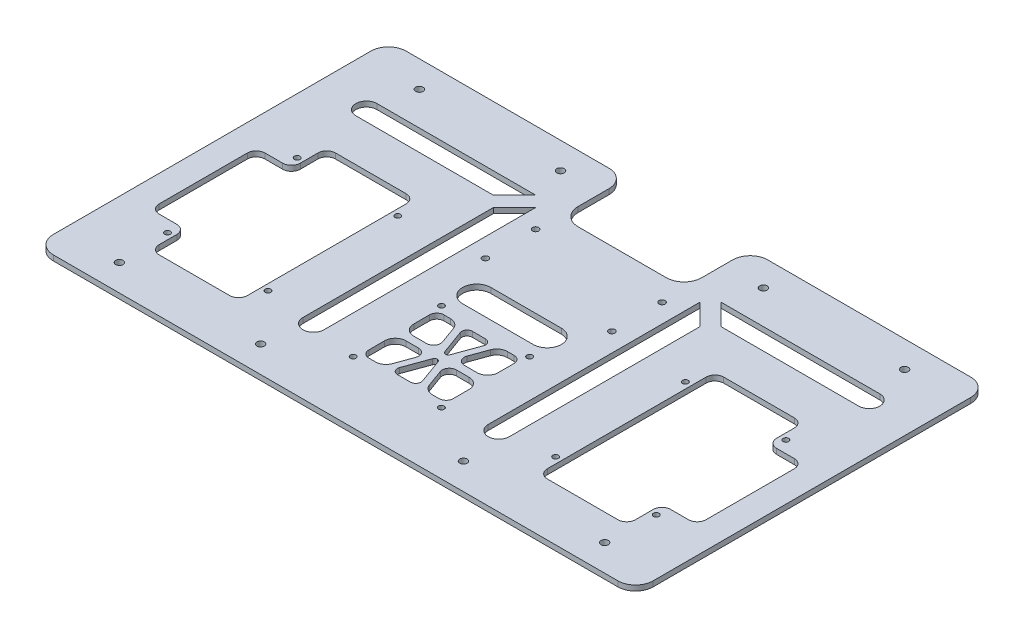
SolidWorks part; units mm, degrees
material "1023 碳钢板 (SS)"
ref_plane "前视基准面" through (0, 0, 0) normal (0, 0, 1) x (1, 0, 0)
ref_plane "上视基准面" through (0, 0, 0) normal (0, 1, 0) x (1, 0, 0)
ref_plane "右视基准面" through (0, 0, 0) normal (1, 0, 0) x (0, 0, -1)
sketch "草图1" plane through (0, 0, 0) normal (0, 1, 0) x (1, 0, 0)
  line L1 (-217.5, 100) -> (217.5, 100)
  line L2 (-217.5, 100) -> (-217.5, -100)
  line L3 (-217.5, -100) -> (217.5, -100)
  line L4 (217.5, 100) -> (217.5, -100)
  line L5 (-217.5, 100) -> (217.5, -100) construction
  line L6 (-217.5, -100) -> (217.5, 100) construction
  point P0 (0, 0)
  dimension "D1" = 200
  dimension "D2" = 435
extrude "凸台-拉伸1" add sketch "草图1" along normal blind 3
sketch "草图2" plane through (0, 3, 0) normal (0, 1, 0) x (1, 0, 0)
  line L0 (0, -1000) -> (0, 49000) construction
  line L1 (217.5, 100) -> (-217.5, 100) construction
  line L2 (81.5, 16.75) -> (138.5, 16.75) construction
  line L3 (81.5, 16.75) -> (81.5, -56.75) construction
  line L4 (81.5, -56.75) -> (138.5, -56.75) construction
  line L5 (138.5, 16.75) -> (138.5, -56.75) construction
  line L6 (81.5, 16.75) -> (138.5, -56.75) construction
  line L7 (81.5, -56.75) -> (138.5, 16.75) construction
  line L8 (-81.5, -56.75) -> (-138.5, 16.75) construction
  line L9 (-81.5, 16.75) -> (-138.5, -56.75) construction
  line L10 (-138.5, 16.75) -> (-138.5, -56.75) construction
  line L11 (-81.5, -56.75) -> (-138.5, -56.75) construction
  line L12 (-81.5, 16.75) -> (-81.5, -56.75) construction
  line L13 (-81.5, 16.75) -> (-138.5, 16.75) construction
  circle A0 centre (138.5, 16.75) radius 1.6
  circle A1 centre (138.5, -56.75) radius 1.6
  circle A2 centre (81.5, -56.75) radius 1.6
  circle A3 centre (81.5, 16.75) radius 1.6
  circle A4 centre (-81.5, 16.75) radius 1.6
  circle A5 centre (-81.5, -56.75) radius 1.6
  circle A6 centre (-138.5, -56.75) radius 1.6
  circle A7 centre (-138.5, 16.75) radius 1.6
  point P1 (110, -20)
  point P22 (-110, -20)
  dimension "D5" = 3.2
  dimension "D6" = 3.2
  dimension "D7" = 3.2
  dimension "D8" = 3.2
  dimension "D1" = 120
  dimension "D2" = 110
  dimension "D3" = 57
  dimension "D4" = 73.5
extrude "切除-拉伸1" cut sketch "草图2" against normal blind 157
sketch "草图3" plane through (0, 3, 0) normal (0, 1, 0) x (1, 0, 0)
  line L0 (-138.5, 16.75) -> (-81.5, 16.75) construction
  line L1 (-110, -923.25) -> (-110, 49076.75) construction
  line L2 (-138.5, 16.75) -> (-81.5, -56.75) construction
  line L3 (0, -1000) -> (0, 49000) construction
  line L4 (-135, 30) -> (-85, 30)
  line L5 (-135, 30) -> (-135, -70)
  line L6 (-135, -70) -> (-85, -70)
  line L7 (-85, 30) -> (-85, -70)
  line L8 (-135, 30) -> (-85, -70) construction
  line L9 (-135, -70) -> (-85, 30) construction
  line L10 (135, -70) -> (85, 30) construction
  line L11 (135, 30) -> (85, -70) construction
  line L12 (138.5, 16.75) -> (81.5, -56.75) construction
  line L13 (138.5, 16.75) -> (81.5, 16.75) construction
  line L14 (85, 30) -> (85, -70)
  line L15 (135, -70) -> (85, -70)
  line L16 (135, 30) -> (135, -70)
  line L17 (135, 30) -> (85, 30)
  point P3 (-110, -20)
  point P5 (-110, 16.75)
  point P24 (110, -20)
  dimension "D1" = 100
  dimension "D2" = 50
extrude "切除-拉伸2" cut sketch "草图3" against normal blind 157
sketch "草图5" plane through (0, 3, 0) normal (0, 1, 0) x (1, 0, 0)
  line L0 (-1060, -20) -> (48940, -20) construction
  line L1 (-135, 30) -> (-135, -70) construction
  line L2 (0, -1000) -> (0, 49000) construction
  line L3 (-155, 10) -> (-135, 10)
  line L4 (-155, 10) -> (-155, -50)
  line L5 (-155, -50) -> (-135, -50)
  line L6 (-135, 10) -> (-135, -50)
  line L7 (-155, 10) -> (-135, -50) construction
  line L8 (-155, -50) -> (-135, 10) construction
  line L9 (155, -50) -> (135, 10) construction
  line L10 (155, 10) -> (135, -50) construction
  line L11 (135, 10) -> (135, -50)
  line L12 (155, -50) -> (135, -50)
  line L13 (155, 10) -> (155, -50)
  line L14 (155, 10) -> (135, 10)
  point P1 (-145, -20)
  point P5 (-135, -20)
  point P17 (145, -20)
  dimension "D1" = 60
  dimension "D2" = 10
extrude "切除-拉伸3" cut sketch "草图5" against normal blind 157
fillet "圆角1" radius 5 16 edges at (155, 1.5, 50) (135, 1.5, 70) (85, 1.5, -30) (85, 1.5, 70) (135, 1.5, 50) (135, 1.5, -10) (135, 1.5, -30) (155, 1.5, -10) (-85, 1.5, 70) (-135, 1.5, 70) (-135, 1.5, 50) (-155, 1.5, 50) (-155, 1.5, -10) (-85, 1.5, -30) (-135, 1.5, -30) (-135, 1.5, -10)
sketch "草图6" plane through (0, 3, 0) normal (0, 1, 0) x (1, 0, 0)
  line L0 (0, -1000) -> (0, 49000) construction
  line L1 (-40, -85) -> (40, -85)
  line L2 (-31.4905, -2.5) -> (31.4905, -2.5)
  line L3 (40, -12.5) -> (40, -85)
  line L4 (31.4905, -2.5) -> (40, -12.5)
  line L5 (-31.4905, -2.5) -> (-40, -12.5)
  line L6 (-40, -12.5) -> (-40, -85)
  line L7 (-217.5, -100) -> (217.5, -100) construction
  point P6 (0, -85)
  point P7 (0, -85)
  point P12 (0, -2.5)
  dimension "D1" = 40
  dimension "D2" = 72.5
  dimension "D3" = 10
  dimension "D4" = 15
extrude "切除-拉伸4" [suppressed] cut sketch "草图6" against normal blind 157
sketch "草图7" plane through (0, 3, 0) normal (0, 1, 0) x (1, 0, 0)
  line L0 (-1068.651, -70) -> (48931.349, -70) construction
  line L1 (-217.5, -100) -> (217.5, -100) construction
  circle A0 centre (55, -70) radius 1.6
  circle A1 centre (-55, -70) radius 1.6
  circle A2 centre (55, -20) radius 1.6
  circle A3 centre (-55, -20) radius 1.6
  dimension "D2" = 3.2
  dimension "D4" = 3.2
  dimension "D7" = 3.2
  dimension "D8" = 3.2
  dimension "D1" = 30
  dimension "D3" = 55
  dimension "D5" = 110
  dimension "D6" = 50
  dimension "D9" = 50
  dimension "D10" = 110
extrude "切除-拉伸5" [suppressed] cut sketch "草图7" against normal blind 157
sketch "草图8" plane through (0, 3, 0) normal (0, 1, 0) x (1, 0, 0)
  line L1 (217.5, -100) -> (217.5, 100) construction
  line L2 (217.5, 100) -> (-217.5, 100) construction
  line L3 (-35.85, 49.25) -> (35.85, 49.25) construction
  line L4 (-35.85, 49.25) -> (-35.85, 20.75) construction
  line L5 (-35.85, 20.75) -> (35.85, 20.75) construction
  line L6 (35.85, 49.25) -> (35.85, 20.75) construction
  line L7 (-35.85, 49.25) -> (35.85, 20.75) construction
  line L8 (-35.85, 20.75) -> (35.85, 49.25) construction
  circle A0 centre (-35.85, 49.25) radius 1.75
  circle A1 centre (35.85, 49.25) radius 1.75
  circle A2 centre (-35.85, 20.75) radius 1.75
  circle A3 centre (35.85, 20.75) radius 1.75
  point P0 (0, 35)
  dimension "D4" = 3.5
  dimension "D5" = 3.5
  dimension "D6" = 3.5
  dimension "D7" = 3.5
  dimension "D1" = 217.5
  dimension "D2" = 71.7
  dimension "D3" = 28.5
  dimension "D8" = 65
sketch "草图9" plane through (0, 3, 0) normal (0, 1, 0) x (1, 0, 0)
  line L0 (-1217.5, -85) -> (48782.5, -85) construction
  line L2 (-217.5, -100) -> (217.5, -100) construction
  line L3 (0, -1000) -> (0, 49000) construction
  line L4 (-1000, 0) -> (49000, 0) construction
  line L5 (-217.5, 100) -> (-217.5, -100) construction
  circle A0 centre (-137.5, -85) radius 2.1
  circle A2 centre (-57.5, -85) radius 2.1
  circle A3 centre (57.5, -85) radius 2.1
  circle A5 centre (137.5, -85) radius 2.1
  circle A6 centre (137.5, 85) radius 2.1
  circle A8 centre (57.5, 85) radius 2.1
  circle A9 centre (-57.5, 85) radius 2.1
  circle A11 centre (-137.5, 85) radius 2.1
  dimension "D2" = 4.2
  dimension "D3" = 80
  dimension "D7" = 4.2
  dimension "D1" = 15
  dimension "D4" = 80
extrude "切除-拉伸6" cut sketch "草图9" against normal blind 10
sketch "草图10" plane through (0, 3, 0) normal (0, 1, 0) x (1, 0, 0)
  line L0 (0, -1000) -> (0, 49000) construction
  line L1 (-217.5, -100) -> (217.5, -100) construction
  line L2 (-25, -15) -> (25, -15) construction
  line L3 (-25, -15) -> (-25, -65) construction
  line L4 (-25, -65) -> (25, -65) construction
  line L5 (25, -15) -> (25, -65) construction
  line L6 (-25, -15) -> (25, -65) construction
  line L7 (-25, -65) -> (25, -15) construction
  circle A0 centre (-25, -15) radius 1.6
  circle A1 centre (25, -15) radius 1.6
  circle A2 centre (25, -65) radius 1.6
  circle A3 centre (-25, -65) radius 1.6
  point P1 (0, -40)
  dimension "D4" = 3.2
  dimension "D5" = 3.2
  dimension "D6" = 3.2
  dimension "D7" = 3.2
  dimension "D1" = 50
  dimension "D2" = 50
  dimension "D3" = 60
extrude "切除-拉伸7" cut sketch "草图10" against normal blind 10
fillet "圆角2" [suppressed] radius 10
extrude "切除-拉伸8" cut sketch "草图8" against normal blind 10
sketch "草图12" plane through (0, 3, 0) normal (0, 1, 0) x (1, 0, 0)
  line L1 (-251.9202, 129.8695) -> (-3.3421, 129.8695)
  line L2 (-251.9202, 129.8695) -> (-251.9202, -149.5666)
  line L3 (-251.9202, -149.5666) -> (-3.3421, -149.5666)
  line L4 (-3.3421, 129.8695) -> (-3.3421, -149.5666)
  line L5 (-3.3421, -53.564) -> (257.665, -53.564)
  line L6 (-3.3421, -53.564) -> (-3.3421, -149.5666)
  line L7 (-3.3421, -149.5666) -> (257.665, -149.5666)
  line L8 (257.665, -53.564) -> (257.665, -149.5666)
  line L9 (-3.3421, 129.8695) -> (241.8074, 129.8695)
  line L10 (-3.3421, 129.8695) -> (-3.3421, 96.8686)
  line L11 (-3.3421, 96.8686) -> (241.8074, 96.8686)
  line L12 (241.8074, 129.8695) -> (241.8074, 96.8686)
extrude "切除-拉伸10" [suppressed] cut sketch "草图12" against normal blind 10 contours L4 L1 L2 L3 | L12 L9 L4 L11 | L8 L5 L4 L7
sketch "草图13" plane through (0, 3, 0) normal (0, 1, 0) x (1, 0, 0)
  line L0 (-1000, 0) -> (49000, 0) construction
  line L1 (-52.5007, 60) -> (-142.5007, 60) construction
  line L2 (-52.5007, 54) -> (-142.5007, 54)
  line L3 (-52.5007, 66) -> (-142.5007, 66)
  line L5 (0, -1000) -> (0, 49000) construction
  line L6 (52.5007, 60) -> (142.5007, 60) construction
  line L7 (52.5007, 54) -> (142.5007, 54)
  line L8 (52.5007, 66) -> (142.5007, 66)
  line L9 (-155, 5) -> (-155, -45) construction
  line L10 (-52.5007, 60) -> (52.5007, 60) construction
  line L11 (-52.5007, 60) -> (-52.5007, -60) construction
  line L12 (-52.5007, -60) -> (52.5007, -60) construction
  line L13 (52.5007, 60) -> (52.5007, -60) construction
  line L14 (-52.5007, 60) -> (52.5007, -60) construction
  line L15 (-52.5007, -60) -> (52.5007, 60) construction
  line L16 (-52.5007, 60) -> (-52.5007, -60) construction
  line L17 (-46.5007, 60) -> (-46.5007, -60)
  line L18 (-58.5007, 60) -> (-58.5007, -60)
  line L19 (52.5007, 60) -> (52.5007, -60) construction
  line L20 (52.5007, 60) -> (52.5007, -60) construction
  line L21 (46.5007, 60) -> (46.5007, -60)
  line L22 (58.5007, 60) -> (58.5007, -60)
  line L23 (-20, 0) -> (20, 0) construction
  line L24 (-20, 8) -> (20, 8)
  line L25 (-20, -8) -> (20, -8)
  line L51 (-223.1142, 125.8648) -> (-170, 125.8648)
  line L52 (-223.1142, 125.8648) -> (-223.1142, -114.639)
  line L53 (-223.1142, -114.639) -> (-170, -114.639)
  line L54 (-170, 125.8648) -> (-170, -114.639)
  line L55 (170, 125.8648) -> (170, -114.639)
  line L56 (223.1142, -114.639) -> (170, -114.639)
  line L57 (223.1142, 125.8648) -> (223.1142, -114.639)
  line L58 (223.1142, 125.8648) -> (170, 125.8648)
  arc A0 (-52.5007, 54) -> (-52.5007, 66) centre (-52.5007, 60) ccw
  arc A1 (-142.5007, 66) -> (-142.5007, 54) centre (-142.5007, 60) ccw
  arc A2 (52.5007, 54) -> (52.5007, 66) centre (52.5007, 60) cw
  arc A3 (142.5007, 66) -> (142.5007, 54) centre (142.5007, 60) cw
  arc A4 (-46.5007, 60) -> (-58.5007, 60) centre (-52.5007, 60) ccw
  arc A5 (-58.5007, -60) -> (-46.5007, -60) centre (-52.5007, -60) ccw
  arc A6 (46.5007, 60) -> (58.5007, 60) centre (52.5007, 60) cw
  arc A7 (58.5007, -60) -> (46.5007, -60) centre (52.5007, -60) cw
  arc A8 (-20, 8) -> (-20, -8) centre (-20, 0) ccw
  arc A9 (20, -8) -> (20, 8) centre (20, 0) ccw
  point P4 (-97.5007, 60)
  point P11 (97.5007, 60)
  point P29 (-52.5007, 0)
  point P34 (52.5007, 0)
  point P41 (0, 0)
  dimension "D2" = 90
  dimension "D7" = 6
  dimension "D10" = 8
  dimension "D3" = 6
  dimension "D4" = 15
  dimension "D5" = 120
  dimension "D6" = 0
  dimension "D9" = 0
extrude "切除-拉伸11" cut sketch "草图13" against normal blind 10
sketch "草图14" plane through (0, 3, 0) normal (0, 1, 0) x (1, 0, 0)
  line L0 (0, -1000) -> (0, 49000) construction
  line L2 (170, 100) -> (-170, 100) construction
  line L3 (-35, 137.5) -> (35, 137.5)
  line L4 (-35, 137.5) -> (-35, 62.5)
  line L5 (-35, 62.5) -> (35, 62.5)
  line L6 (35, 137.5) -> (35, 62.5)
  line L7 (-35, 137.5) -> (35, 62.5) construction
  line L8 (-35, 62.5) -> (35, 137.5) construction
  point P1 (0, 100)
  dimension "D1" = 75
  dimension "D2" = 70
extrude "切除-拉伸12" cut sketch "草图14" against normal blind 64.5 contours L6 L3 L4 L5
fillet "圆角4" radius 10 8 edges at (-35, 1.5, -62.5) (35, 1.5, -62.5) (-35, 1.5, -100) (35, 1.5, -100) (170, 1.5, 100) (-170, 1.5, 100) (170, 1.5, -100) (-170, 1.5, -100)
sketch "草图15" plane through (0, 3, 0) normal (0, 1, 0) x (1, 0, 0)
  line L3 (6.5346, -57.2239) -> (1.5635, -43.566)
  line L4 (-23.9154, -22.75) -> (-23.9154, -31.75)
  line L5 (-17.9154, -37.75) -> (-10.7126, -37.75)
  line L6 (-6.9538, -32.3819) -> (-10.4785, -22.6979)
  line L7 (-16.1167, -18.75) -> (-19.9154, -18.75)
  line L8 (-23.9154, -22.75) -> (-23.9154, -31.75)
  line L9 (-17.9154, -37.75) -> (-10.7126, -37.75)
  line L10 (-6.9538, -32.3819) -> (-10.4785, -22.6979)
  line L11 (-16.1167, -18.75) -> (-19.9154, -18.75)
  line L12 (-10.4785, -57.3021) -> (-6.9538, -47.6181)
  line L13 (-19.9154, -61.25) -> (-16.1167, -61.25)
  line L14 (-23.9154, -48.25) -> (-23.9154, -57.25)
  line L15 (-10.7126, -42.25) -> (-17.9154, -42.25)
  line L16 (-10.4785, -57.3021) -> (-6.9538, -47.6181)
  line L17 (-19.9154, -61.25) -> (-16.1167, -61.25)
  line L18 (-23.9154, -48.25) -> (-23.9154, -57.25)
  line L19 (-10.7126, -42.25) -> (-17.9154, -42.25)
  line L20 (-1.5635, -43.566) -> (-6.5346, -57.2239)
  line L21 (-3.7156, -61.25) -> (3.7156, -61.25)
  line L22 (6.5346, -57.2239) -> (1.5635, -43.566)
  line L23 (-1.5635, -43.566) -> (-6.5346, -57.2239)
  line L24 (-3.7156, -61.25) -> (3.7156, -61.25)
  line L25 (1.5635, -36.434) -> (6.5346, -22.7761)
  line L26 (23.9154, -31.75) -> (23.9154, -22.75)
  line L27 (10.7126, -37.75) -> (17.9154, -37.75)
  line L28 (10.4785, -22.6979) -> (6.9538, -32.3819)
  line L29 (19.9154, -18.75) -> (16.1167, -18.75)
  line L30 (23.9154, -31.75) -> (23.9154, -22.75)
  line L31 (10.7126, -37.75) -> (17.9154, -37.75)
  line L32 (10.4785, -22.6979) -> (6.9538, -32.3819)
  line L33 (19.9154, -18.75) -> (16.1167, -18.75)
  line L34 (-6.5346, -22.7761) -> (-1.5635, -36.434)
  line L35 (3.7156, -18.75) -> (-3.7156, -18.75)
  line L36 (1.5635, -36.434) -> (6.5346, -22.7761)
  line L37 (-6.5346, -22.7761) -> (-1.5635, -36.434)
  line L38 (3.7156, -18.75) -> (-3.7156, -18.75)
  line L40 (23.9154, -57.25) -> (23.9154, -48.25)
  line L41 (17.9154, -42.25) -> (10.7126, -42.25)
  line L42 (6.9538, -47.6181) -> (10.4785, -57.3021)
  line L43 (16.1167, -61.25) -> (19.9154, -61.25)
  line L44 (23.9154, -57.25) -> (23.9154, -48.25)
  line L45 (17.9154, -42.25) -> (10.7126, -42.25)
  line L46 (6.9538, -47.6181) -> (10.4785, -57.3021)
  line L47 (16.1167, -61.25) -> (19.9154, -61.25)
  arc A0 (-23.9154, -31.75) -> (-17.9154, -37.75) centre (-17.9154, -31.75) ccw construction
  arc A1 (-23.9154, -31.75) -> (-17.9154, -37.75) centre (-17.9154, -31.75) ccw
  arc A6 (-19.9154, -18.75) -> (-23.9154, -22.75) centre (-19.9154, -22.75) ccw
  arc A7 (-23.9154, -31.75) -> (-17.9154, -37.75) centre (-17.9154, -31.75) ccw
  arc A8 (-10.7126, -37.75) -> (-6.9538, -32.3819) centre (-10.7126, -33.75) ccw
  arc A9 (-10.4785, -22.6979) -> (-16.1167, -18.75) centre (-16.1167, -24.75) ccw
  arc A10 (-19.9154, -18.75) -> (-23.9154, -22.75) centre (-19.9154, -22.75) ccw
  arc A11 (-23.9154, -31.75) -> (-17.9154, -37.75) centre (-17.9154, -31.75) ccw
  arc A12 (-10.7126, -37.75) -> (-6.9538, -32.3819) centre (-10.7126, -33.75) ccw
  arc A13 (-10.4785, -22.6979) -> (-16.1167, -18.75) centre (-16.1167, -24.75) ccw
  arc A14 (-6.9538, -47.6181) -> (-10.7126, -42.25) centre (-10.7126, -46.25) ccw
  arc A15 (-16.1167, -61.25) -> (-10.4785, -57.3021) centre (-16.1167, -55.25) ccw
  arc A16 (-23.9154, -57.25) -> (-19.9154, -61.25) centre (-19.9154, -57.25) ccw
  arc A17 (-17.9154, -42.25) -> (-23.9154, -48.25) centre (-17.9154, -48.25) ccw
  arc A18 (-6.9538, -47.6181) -> (-10.7126, -42.25) centre (-10.7126, -46.25) ccw
  arc A19 (-16.1167, -61.25) -> (-10.4785, -57.3021) centre (-16.1167, -55.25) ccw
  arc A20 (-23.9154, -57.25) -> (-19.9154, -61.25) centre (-19.9154, -57.25) ccw
  arc A21 (-17.9154, -42.25) -> (-23.9154, -48.25) centre (-17.9154, -48.25) ccw
  arc A22 (1.5635, -43.566) -> (0, -42.2751) centre (-0.3158, -44.25) ccw
  arc A23 (0, -42.2751) -> (-1.5635, -43.566) centre (0.3158, -44.25) ccw
  arc A24 (-6.5346, -57.2239) -> (-3.7156, -61.25) centre (-3.7156, -58.25) ccw
  arc A25 (3.7156, -61.25) -> (6.5346, -57.2239) centre (3.7156, -58.25) ccw
  arc A26 (1.5635, -43.566) -> (0, -42.2751) centre (-0.3158, -44.25) ccw
  arc A27 (0, -42.2751) -> (-1.5635, -43.566) centre (0.3158, -44.25) ccw
  arc A28 (-6.5346, -57.2239) -> (-3.7156, -61.25) centre (-3.7156, -58.25) ccw
  arc A29 (3.7156, -61.25) -> (6.5346, -57.2239) centre (3.7156, -58.25) ccw
  arc A30 (23.9154, -22.75) -> (19.9154, -18.75) centre (19.9154, -22.75) ccw
  arc A31 (17.9154, -37.75) -> (23.9154, -31.75) centre (17.9154, -31.75) ccw
  arc A32 (6.9538, -32.3819) -> (10.7126, -37.75) centre (10.7126, -33.75) ccw
  arc A33 (16.1167, -18.75) -> (10.4785, -22.6979) centre (16.1167, -24.75) ccw
  arc A34 (23.9154, -22.75) -> (19.9154, -18.75) centre (19.9154, -22.75) ccw
  arc A35 (17.9154, -37.75) -> (23.9154, -31.75) centre (17.9154, -31.75) ccw
  arc A36 (6.9538, -32.3819) -> (10.7126, -37.75) centre (10.7126, -33.75) ccw
  arc A37 (16.1167, -18.75) -> (10.4785, -22.6979) centre (16.1167, -24.75) ccw
  arc A38 (6.5346, -22.7761) -> (3.7156, -18.75) centre (3.7156, -21.75) ccw
  arc A39 (0, -37.7249) -> (1.5635, -36.434) centre (-0.3158, -35.75) ccw
  arc A40 (-1.5635, -36.434) -> (0, -37.7249) centre (0.3158, -35.75) ccw
  arc A41 (-3.7156, -18.75) -> (-6.5346, -22.7761) centre (-3.7156, -21.75) ccw
  arc A42 (6.5346, -22.7761) -> (3.7156, -18.75) centre (3.7156, -21.75) ccw
  arc A43 (0, -37.7249) -> (1.5635, -36.434) centre (-0.3158, -35.75) ccw
  arc A44 (-1.5635, -36.434) -> (0, -37.7249) centre (0.3158, -35.75) ccw
  arc A45 (-3.7156, -18.75) -> (-6.5346, -22.7761) centre (-3.7156, -21.75) ccw
  arc A46 (19.9154, -61.25) -> (23.9154, -57.25) centre (19.9154, -57.25) ccw
  arc A47 (23.9154, -48.25) -> (17.9154, -42.25) centre (17.9154, -48.25) ccw
  arc A48 (10.7126, -42.25) -> (6.9538, -47.6181) centre (10.7126, -46.25) ccw
  arc A49 (10.4785, -57.3021) -> (16.1167, -61.25) centre (16.1167, -55.25) ccw
  arc A50 (19.9154, -61.25) -> (23.9154, -57.25) centre (19.9154, -57.25) ccw
  arc A51 (23.9154, -48.25) -> (17.9154, -42.25) centre (17.9154, -48.25) ccw
  arc A52 (10.7126, -42.25) -> (6.9538, -47.6181) centre (10.7126, -46.25) ccw
  arc A53 (10.4785, -57.3021) -> (16.1167, -61.25) centre (16.1167, -55.25) ccw
  dimension "D1" = 0
  dimension "D2" = 0
  dimension "D3" = 0
  dimension "D4" = 0
  dimension "D5" = 0
  dimension "D6" = 0
extrude "切除-拉伸13" cut sketch "草图15" against normal blind 10 contours L10 A13 L11 A10 L8 A1 L9 A12 | L38 A45 L37 A44 A43 L36 A42 | L33 A37 L32 A36 L31 A35 L30 A34 | L46 A53 L47 A50 L44 A51 L45 A52 | L24 A29 L22 A26 A27 L23 A28 | L19 A21 L18 A20 L17 A19 L16 A18
sketch "草图16" plane through (0, 3, 0) normal (0, 1, 0) x (1, 0, 0)
  line L0 (-52.5007, 66) -> (-64.5007, 54)
  line L1 (-58.5007, 54) -> (-142.5007, 54) construction
  line L2 (-46.5007, 60) -> (-58.5007, 48)
  line L3 (-58.5007, 54) -> (-58.5007, -60) construction
  line L4 (0, 0) -> (0, 64.5421) construction
  line L5 (-64.5007, 54) -> (-58.5007, 54)
  line L6 (-58.5007, 54) -> (-58.5007, 48)
  line L7 (58.5007, 54) -> (58.5007, 48)
  line L8 (64.5007, 54) -> (58.5007, 54)
  line L9 (46.5007, 60) -> (58.5007, 48)
  line L10 (52.5007, 66) -> (64.5007, 54)
  arc A0 (-46.5007, 60) -> (-52.5007, 66) centre (-52.5007, 60) ccw construction
  arc A1 (-46.5007, 60) -> (-52.5007, 66) centre (-52.5007, 60) ccw
  arc A2 (46.5007, 60) -> (52.5007, 66) centre (52.5007, 60) cw
  dimension "D1" = 45
  dimension "D2" = 45
extrude "凸台-拉伸3" add sketch "草图16" against normal up to surface (3 mm away) contours L2 A1 L0 L5 L6 | A2 L9 L7 L8 L10 up to face at (16.2469, 0, 27.8854)
